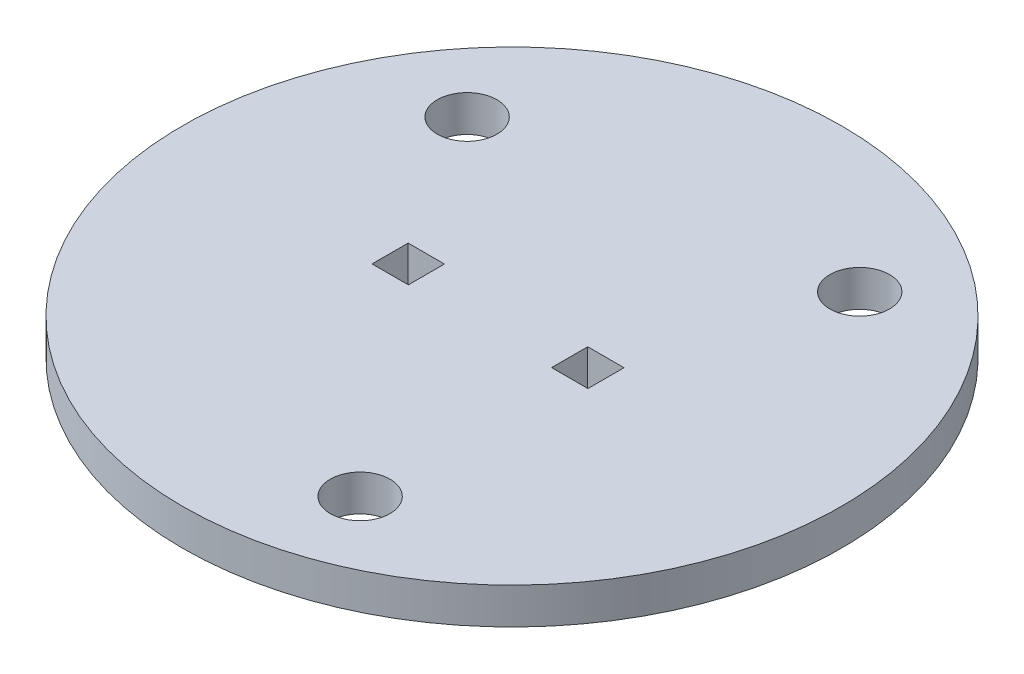
SolidWorks part; units mm, degrees
ref_plane "Front Plane" through (0, 0, 0) normal (0, 0, 1) x (1, 0, 0)
ref_plane "Top Plane" through (0, 0, 0) normal (0, 1, 0) x (1, 0, 0)
ref_plane "Right Plane" through (0, 0, 0) normal (1, 0, 0) x (0, 0, -1)
sketch "Sketch1" plane through (0, 0, 0) normal (0, 1, 0) x (1, 0, 0)
  line L1 (0, 0) -> (101.6, 0)
  line L2 (0, 0) -> (0, 101.6)
  line L3 (0, 101.6) -> (101.6, 101.6)
  line L4 (101.6, 0) -> (101.6, 101.6)
  line L5 (0, 0) -> (101.6, 101.6) construction
  line L6 (0, 101.6) -> (101.6, 0) construction
  point P4 (50.8, 50.8)
  dimension "D1" = 101.6
  dimension "D2" = 101.6
extrude "Boss-Extrude1" add sketch "Sketch1" along normal blind 4.826
ref_point "Point1"
sketch "Sketch2" plane through (0, 4.826, 0) normal (0, 1, 0) x (1, 0, 0)
  circle A4 centre (50.8, 50.8) radius 43.815
extrude "Cut-Extrude1" cut sketch "Sketch2" against normal through all flip side to cut
sketch "Sketch4" plane through (0, 4.826, 0) normal (0, 1, 0) x (1, 0, 0)
  circle A3 centre (61.468, 19.939) radius 3.9688
  circle A4 centre (71.12, 76.708) radius 3.9688
  circle A5 centre (24.892, 70.739) radius 3.9688
extrude "Cut-Extrude3" cut sketch "Sketch4" against normal through all
sketch "Sketch5" plane through (0, 4.826, 0) normal (0, 1, 0) x (1, 0, 0)
  line L4 (35.4936, 47.4987) -> (40.3196, 47.4987)
  line L5 (35.4936, 52.2987) -> (35.4936, 47.4987)
  line L6 (35.4936, 52.2987) -> (40.3196, 52.2987)
  line L7 (40.3196, 52.2987) -> (40.3196, 47.4987)
  line L16 (59.3696, 52.2987) -> (59.3696, 47.4987)
  line L17 (59.3696, 47.4987) -> (64.1956, 47.4987)
  line L18 (64.1956, 47.4987) -> (64.1956, 52.2987)
  line L19 (64.1956, 52.2987) -> (59.3696, 52.2987)
extrude "Cut-Extrude4" cut sketch "Sketch5" against normal through all
equation "\"MDF\"= 4.8mm"
equation "\"Foamcore\"= 4.6mm"
equation "\"GMaterial\"= \"MDF\""
equation "\"PCB\" = 1.6mm"
equation "\"BaseWidth\" = 10in"
equation "\"SkidLength\" = 1in"
equation "\"SkidClearance\" = 0.4in"
equation "\"MotorMountLength\" = 2in"
equation "\"MotorMountWidth\" = \"GMaterial\""
equation "\"MotorMountHeight\" = 2.25in"
equation "\"UnoStackWidth\" = 77.4mm"
equation "\"UnoStackLength\" = 79.8mm"
equation "\"UnoStackHeight\" = 34.2mm"
equation "\"TallHexRiserHeight\" = 22.2mm"
equation "\"PingPongBallSize\" = 40mm"
equation "\"BarrelLength\" = 9in"
equation "\"BarrelSize\" = \"PingPongBallSize\""
equation "\"PlatformLength\" = 4in"
equation "\"PlatformWidth\" = 6in"
equation "\"WheelDiameter\"=2.99213"
equation "\"ServoMountHeight\"=2.49223"
equation "\"ServoGearHeight\" = 0.95330261in"
equation "\"ServoMountLength\"= 1.53774"
equation "\"PivotHoleRadius\"= 0.616358"
equation "\"PlatformMountHeight\" = 3.19"
equation "\"TensionOffSet\"= .3mm"
equation "\"MotorMountWedge\"=0.333333"
equation "\"LaserCutterOffset\"= .3mm"
equation "\"BumperWidth\"=11"
equation "\"PitcherWheelCompression\" = 2.5mm"
equation "\"PitchingWheelWidth\" = 26.2mm"
equation "\"PitchingWheelDiameter\" = 65.5mm"
equation "\"PitchingWheelMountOffset\" = 8.4mm"
equation "\"PitchingWheelInnerDiameter\" = 45.5mm"
equation "\"PitchingWheelBoltShoulder\" = 4.5mm"
equation "\"BrassCouplingLength\" = 18mm"
equation "\"PitchingMotorHeight\" = 57.0mm"
equation "\"PitchingMotorShaftTopHeight\" = \"PitchingMotorHeight\" - 44.1mm"
equation "\"PitchingMotorBodyHeight\" = 38mm"
equation "\"PitchingMotorTopShoulderHeight\" = 40.6mm - \"PitchingMotorBodyHeight\" "
equation "\"PitchingMotorBottomShoulderHeight\" = 40.2mm - \"PitchingMotorBodyHeight\""
equation "\"PitchingMotorBottomShaftHeight\" = \"PitchingMotorHeight\" - \"PitchingMotorShaftTopHeight\" - \"PitchingMotorTopShoulderHeight\" - \"PitchingMotorBodyHeight\" - \"PitchingMotorBottomShoulderHeight\""
equation "\"PitchingMotorShaftDiameter\" = 2.2mm"
equation "\"PitchingMotorBodyDiameter\" = 27.4mm"
equation "\"PitchingMotorTopShoulderDiameter\" = 9.8mm"
equation "\"PitchingMotorBottomShoulderDiameter\" = 9.8mm"
equation "\"BrassCouplingHexSize\" = 12mm"
equation "\"BrassCouplingBoreSize\" = 3.17mm"
equation "\"PitchingMotorMountingHoleDistance\" = 16mm"
equation "\"Acrylic\" = 4.4mm"
equation "\"PitchingMotorDistance\" = \"PitchingWheelDiameter\" + \"PingPongBallSize\" - \"PitcherWheelCompression\"*2"
equation "\"PitchingMotorPlatformOffset\"=1"
equation "\"ServoPlatformOffset\"=1.64173"
equation "\"BallBearingDiameter\" = 22mm"
equation "\"BallBearingWidth\" = 9mm"
equation "\"BallBearingHexShoulder\" = 9mm - 5.9mm"
equation "\"BallBearingHexSize\" = .36in"
equation "\"PlatformMountFootLength\"=0.857143"
equation "\"WheelWidth\"= 26mm"
equation "\"ServoMountReductionBackHeight\"=2.25"
equation "\"PlatformBottomWidthThird\" =  0.857143in"
equation "\"PlatformMountBackReductionHeight\"= 2.5in"
equation "\"PlatformMountBackReductionWidth\"= 3/7in"
equation "\"PlatformMountFrontReductionWidth\" =  1.46226in"
equation "\"PlatformMountFrontReductionHeight\" = 2.5in"
